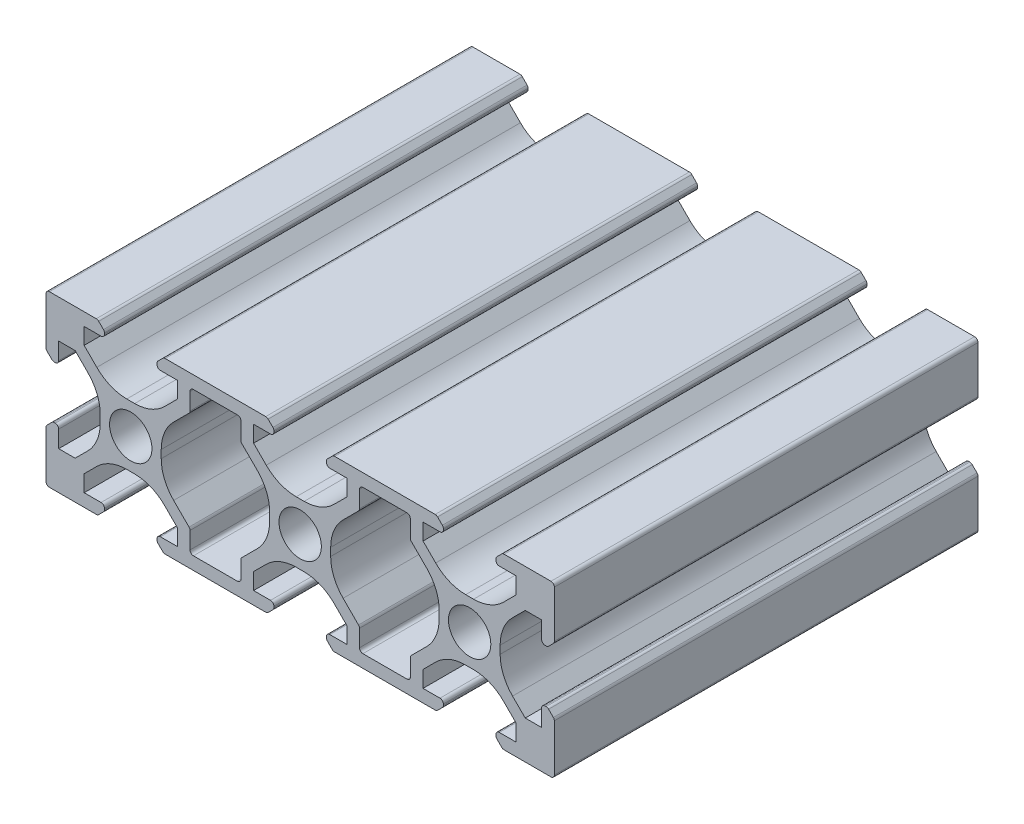
SolidWorks part; units mm, degrees
material "6063-T83"
ref_plane "Plano frontal" through (0, 0, 0) normal (0, 0, 1) x (1, 0, 0)
ref_plane "Plano superior" through (0, 0, 0) normal (0, 1, 0) x (1, 0, 0)
ref_plane "Plano direito" through (0, 0, 0) normal (1, 0, 0) x (0, 0, -1)
sketch "Esboço1" plane through (0, 0, 0) normal (0, 0, 1) x (1, 0, 0)
  line L0 (-9.0343, 3.1) -> (-8.9, 3.1)
  line L3 (-10, 10) -> (-4.0657, 10)
  line L5 (-10, -10) -> (10, 10) construction
  line L6 (-10, 10) -> (10, -10) construction
  line L7 (-8.5, 3.5) -> (-8.5, 5.5)
  line L8 (-10, 0) -> (10, 0) construction
  line L9 (0, 10) -> (0, -10) construction
  line L12 (-8.5, 5.5) -> (-6.5607, 5.5)
  line L15 (-6.5607, 5.5) -> (-5.0645, 4.0038)
  line L16 (-3.6, 0.4683) -> (-3.6, 0)
  line L17 (-0.4683, 3.6) -> (0, 3.6)
  line L18 (-5.5, 6.5607) -> (-4.0038, 5.0645)
  line L21 (-5.5, 8.5) -> (-5.5, 6.5607)
  line L24 (-3.5, 8.5) -> (-5.5, 8.5)
  line L25 (-3.1, 9.0343) -> (-3.1, 8.9)
  line L44 (-10, 4.0657) -> (-10, 10)
  line L45 (-9.8828, 3.7828) -> (-9.3172, 3.2172)
  line L46 (-3.7828, 9.8828) -> (-3.2172, 9.3172)
  line L47 (-3.6, 0) -> (-2.5, 0)
  line L48 (0, 3.6) -> (0, 2.5)
  arc A0 (-3.5, 8.5) -> (-3.1, 8.9) centre (-3.5, 8.9) ccw
  arc A1 (-3.7828, 9.8828) -> (-4.0657, 10) centre (-4.0657, 9.6) ccw
  arc A2 (-10, 4.0657) -> (-9.8828, 3.7828) centre (-9.6, 4.0657) ccw
  arc A3 (-8.5, 3.5) -> (-8.9, 3.1) centre (-8.9, 3.5) cw
  arc A4 (-3.2172, 9.3172) -> (-3.1, 9.0343) centre (-3.5, 9.0343) cw
  arc A5 (-9.3172, 3.2172) -> (-9.0343, 3.1) centre (-9.0343, 3.5) ccw
  arc A6 (-3.6, 0.4683) -> (-5.0645, 4.0038) centre (-8.6, 0.4683) ccw
  arc A7 (-4.0038, 5.0645) -> (-0.4683, 3.6) centre (-0.4683, 8.6) ccw
  circle A8 centre (0, 0) radius 2.5
  point P6 (-10, 3.1)
  point P28 (-3.1, 8.5)
  point P31 (-3.1, 10)
  point P33 (-3.9, 10)
  point P36 (-10, 3.9)
  point P39 (-8.5, 3.1)
  point P42 (-3.1, 9.2)
  point P45 (-9.2, 3.1)
  point P48 (-3.6, 2.5393)
  point P51 (-2.5393, 3.6)
  dimension "D5" = 10
  dimension "D9" = 0.4
  dimension "D10" = 0.4
  dimension "D11" = 5
  dimension "D12" = 5
  dimension "D13" = 5
  dimension "D1" = 6.9
  dimension "D2" = 1.5
  dimension "D3" = 3.6
  dimension "D4" = 1.5
  dimension "D6" = 2.4
  dimension "D7" = 3.6
  dimension "D8" = 45
extrude "Ressalto-extrusão1" add sketch "Esboço1" along normal blind 50
sketch "Esboço3" plane through (0, 0, 0) normal (1, 0, 0) x (0, 0, -1)
  line L0 (0, 0) -> (-1000, 0) construction
  dimension "D1" = 1000
pattern_circular "PadrãoCircular1" count 4 over 360 about axis through (0, 0, 0) along (0, 0, 1) of "Ressalto-extrusão1"
pattern_linear "Padrão linear1" count 3 spacing 20 along (1, 0, 0) of "Ressalto-extrusão1", "PadrãoCircular1"
sketch "Esboço4" plane through (0, 0, 0) normal (0, 0, -1) x (-1, 0, 0)
  line L0 (-13.4393, 5.5) -> (-13, 5.9393)
  line L1 (-13, 8.5) -> (-13, 5.9393)
  line L2 (-10, 10) -> (-10, -10) construction
  line L3 (-4.0657, 10) -> (-15.9343, 10) construction
  line L4 (-15.9343, -10) -> (-4.0657, -10) construction
  line L5 (-11.5, 5.5) -> (-13.4393, 5.5) construction
  line L6 (-14.5, 8.5) -> (-14.5, 6.5607) construction
  line L7 (-7, 8.5) -> (-7, 5.9393)
  line L8 (-6.5607, 5.5) -> (-7, 5.9393)
  line L9 (-13, 8.5) -> (-7, 8.5)
  line L10 (-20, 0) -> (0, 0) construction
  line L11 (-13, -8.5) -> (-7, -8.5)
  line L12 (-6.5607, -5.5) -> (-7, -5.9393)
  line L13 (-7, -8.5) -> (-7, -5.9393)
  line L14 (-13, -8.5) -> (-13, -5.9393)
  line L15 (-13.4393, -5.5) -> (-13, -5.9393)
  line L16 (-13.4393, 5.5) -> (-13.4393, -5.5)
  line L17 (-6.5607, -5.5) -> (-6.5607, 5.5)
  line L31 (-40, 0) -> (-20, 0) construction
  line L32 (-33.4393, 5.5) -> (-33, 5.9393) [skipped]
  line L33 (-33, 8.5) -> (-33, 5.9393) [skipped]
  line L34 (-27, 8.5) -> (-27, 5.9393) [skipped]
  line L35 (-26.5607, 5.5) -> (-27, 5.9393) [skipped]
  line L36 (-33, 8.5) -> (-27, 8.5) [skipped]
  line L37 (-33, -8.5) -> (-27, -8.5) [skipped]
  line L38 (-26.5607, -5.5) -> (-27, -5.9393) [skipped]
  line L39 (-27, -8.5) -> (-27, -5.9393) [skipped]
  line L40 (-33, -8.5) -> (-33, -5.9393) [skipped]
  line L41 (-33.4393, -5.5) -> (-33, -5.9393) [skipped]
  line L42 (-33.4393, 5.5) -> (-33.4393, -5.5) [skipped]
  line L43 (-26.5607, -5.5) -> (-26.5607, 5.5) [skipped]
  line L44 (-30, 10) -> (-30, -10) construction
  dimension "D1" = 45
  dimension "D2" = 1.5
  dimension "D3" = 1.5
  dimension "D4" = 2
extrude "Corte-extrusão1" cut sketch "Esboço4" against normal through all
pattern_linear "Padrão linear2" count 2 spacing 20 along (1, 0, 0) of "Corte-extrusão1"
fillet "Filete1" radius 0.4 16 edges at (13, -5.9393, 25) (13, -8.5, 25) (7, -8.5, 25) (7, -5.9393, 25) (7, 8.5, 25) (7, 5.9393, 25) (13, 8.5, 25) (13, 5.9393, 25) (27, -8.5, 25) (27, -5.9393, 25) (27, 8.5, 25) (27, 5.9393, 25) (33, 8.5, 25) (33, -8.5, 25) (33, -5.9393, 25) (33, 5.9393, 25)
fillet "Filete2" radius 0.4 4 edges at (-10, 10, 25) (50, -10, 25) (50, 10, 25) (-10, -10, 25)
